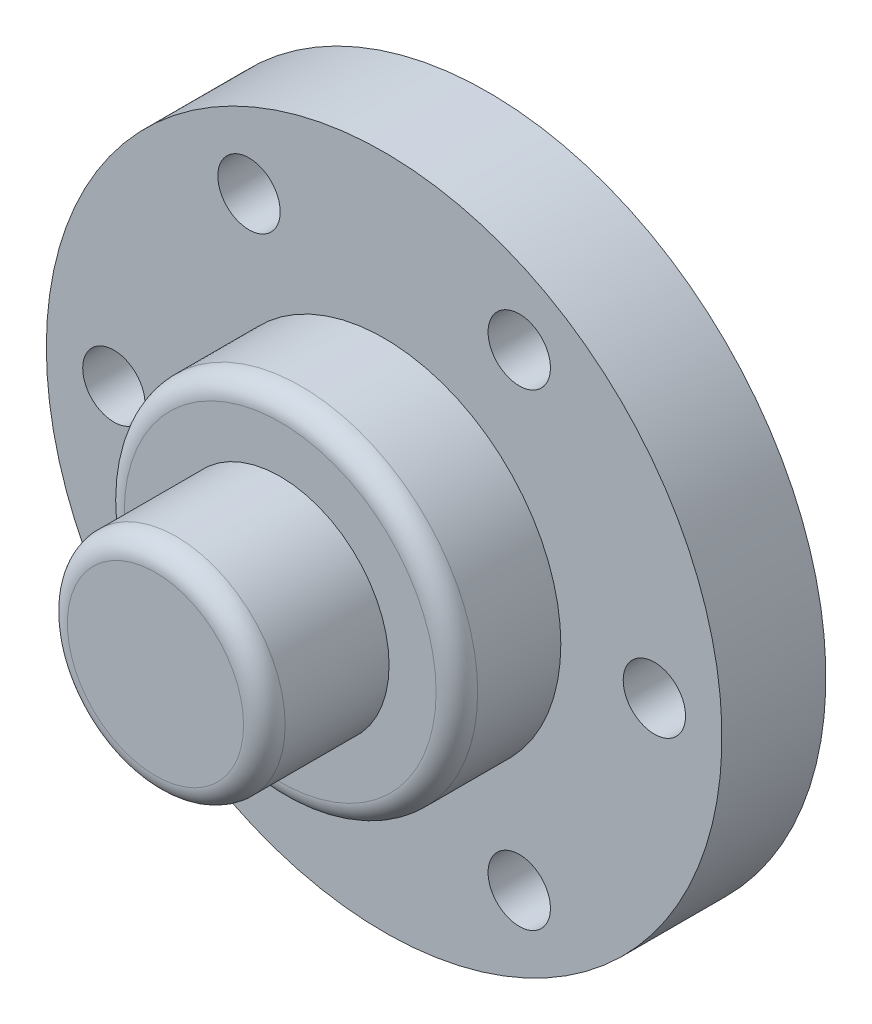
SolidWorks part; units mm, degrees
ref_plane "Front Plane" through (0, 0, 0) normal (0, 0, 1) x (1, 0, 0)
ref_plane "Top Plane" through (0, 0, 0) normal (0, 1, 0) x (1, 0, 0)
ref_plane "Right Plane" through (0, 0, 0) normal (1, 0, 0) x (0, 0, -1)
sketch "Sketch1" plane through (0, 0, 0) normal (0, 0, 1) x (1, 0, 0)
  circle A0 centre (0, 0) radius 17
  dimension "D1" = 34
extrude "Boss-Extrude1" add sketch "Sketch1" along normal blind 10
sketch "Sketch2" plane through (0, 0, 10) normal (0, 0, 1) x (1, 0, 0)
  circle A0 centre (0, 0) radius 10.475
  dimension "D1" = 20.95
extrude "Boss-Extrude2" add sketch "Sketch2" along normal blind 12
fillet "Fillet1" radius 2 2 edges at (10.475, 0, 22) (17, 0, 10)
sketch "Sketch3" plane through (0, 0, 0) normal (0, 0, -1) x (-1, 0, 0)
  circle A0 centre (0, 0) radius 32.5
  dimension "D1" = 65
extrude "Boss-Extrude3" add sketch "Sketch3" along normal blind 10
sketch "Sketch4" plane through (0, 0, -10) normal (0, 0, -1) x (-1, 0, 0)
  line L0 (-43.89, 0) -> (55.0484, 0) construction
  circle A0 centre (26, 0) radius 3
  circle A1 centre (13, -22.5167) radius 3
  circle A2 centre (0, 0) radius 32.5 construction
  circle A4 centre (-13, -22.5167) radius 3
  circle A5 centre (-26, 0) radius 3
  circle A6 centre (-13, 22.5167) radius 3
  circle A7 centre (13, 22.5167) radius 3
  point P21 (0, 0)
  dimension "D1" = 6
  dimension "D2" = 26
  dimension "D3" = 6
extrude "Cut-Extrude1" cut sketch "Sketch4" against normal through all
